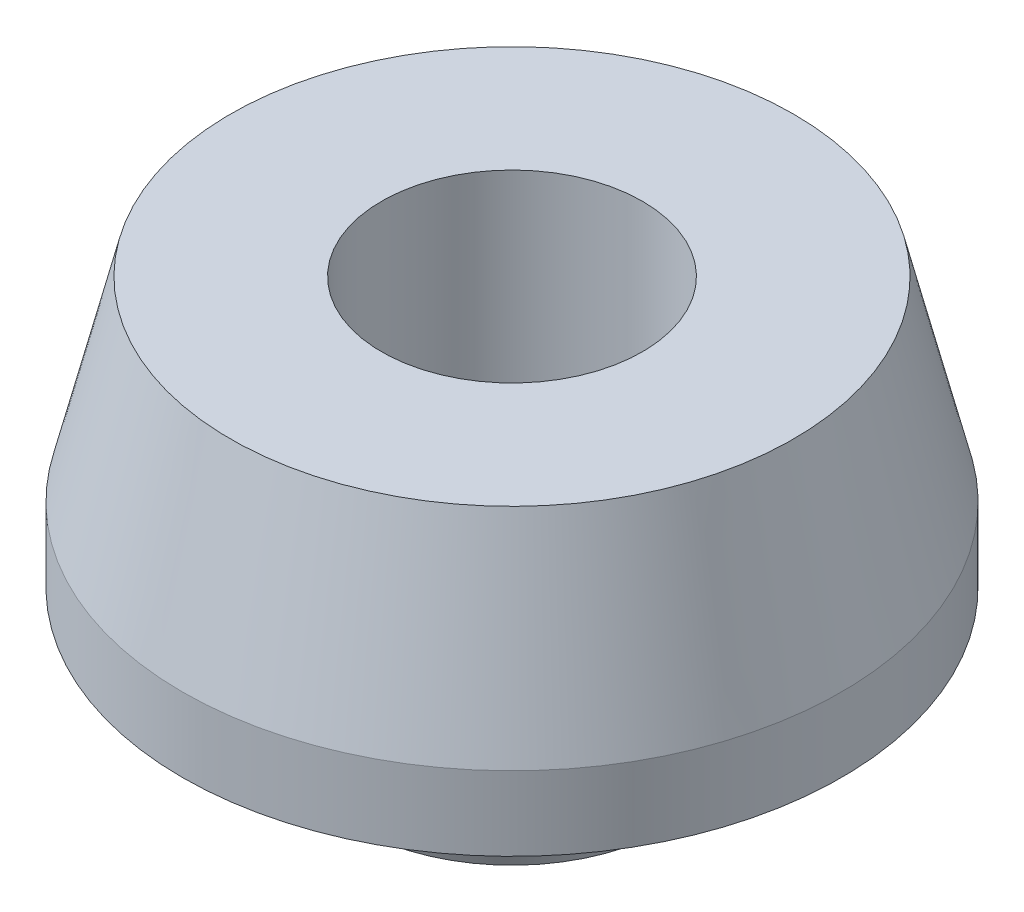
SolidWorks part; units mm, degrees
ref_plane "Front Plane" through (0, 0, 0) normal (0, 0, 1) x (1, 0, 0)
ref_plane "Top Plane" through (0, 0, 0) normal (0, 1, 0) x (1, 0, 0)
ref_plane "Right Plane" through (0, 0, 0) normal (1, 0, 0) x (0, 0, -1)
sketch "Sketch1" plane through (0, 0, 0) normal (0, 0, 1) x (1, 0, 0)
  line L0 (0, 0) -> (0, 14.5) construction
  line L1 (4.75, 1.9803) -> (4.75, 16.4803)
  line L2 (4.75, 16.4803) -> (10.25, 16.4803)
  line L3 (10.25, 16.4803) -> (12, 9.3803)
  line L4 (12, 9.3803) -> (12, 6.6803)
  line L5 (12, 6.6803) -> (7.25, 6.6803)
  line L6 (7.25, 6.6803) -> (5.75, 1.9803)
  line L7 (5.75, 1.9803) -> (4.75, 1.9803)
  dimension "D1" = 9.8
  dimension "D2" = 5.5
  dimension "D3" = 2.7
  dimension "D4" = 14.5
  dimension "D5" = 1
  dimension "D6" = 4.75
  dimension "D7" = 12
  dimension "D8" = 10.25
revolve "Revolve1" add sketch "Sketch1" angle 360 about L0
